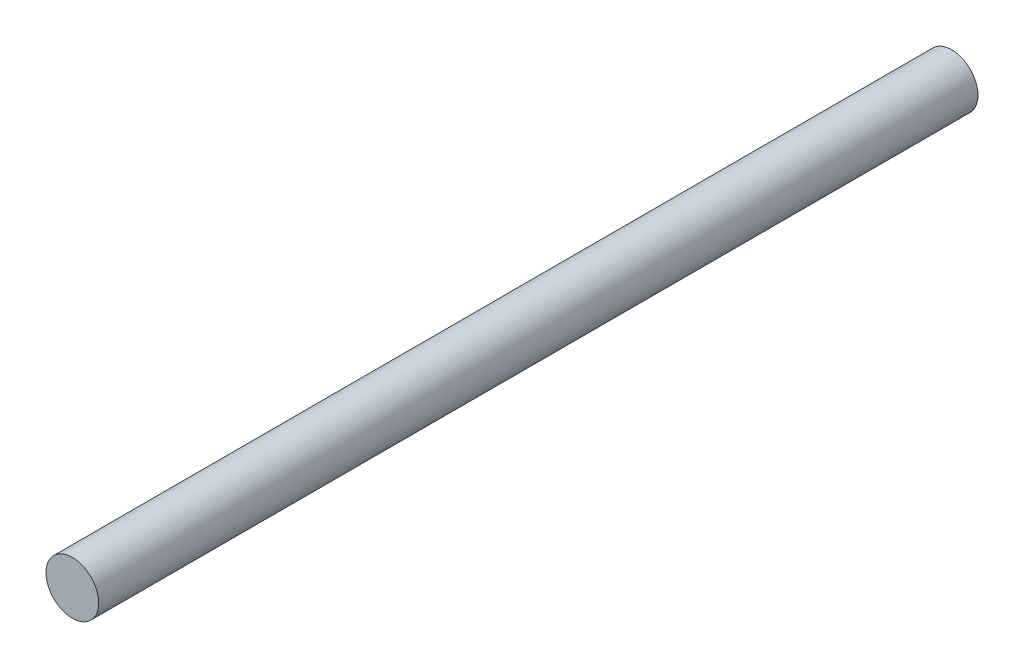
SolidWorks part; units mm, degrees
ref_plane "Front Plane" through (0, 0, 0) normal (0, 0, 1) x (1, 0, 0)
ref_plane "Top Plane" through (0, 0, 0) normal (0, 1, 0) x (1, 0, 0)
ref_plane "Right Plane" through (0, 0, 0) normal (1, 0, 0) x (0, 0, -1)
sketch "Sketch1" plane through (0, 0, 0) normal (0, 0, 1) x (1, 0, 0)
  circle A0 centre (0, 0) radius 7.5
  dimension "D1" = 15
extrude "Boss-Extrude1" add sketch "Sketch1" along normal blind 250
